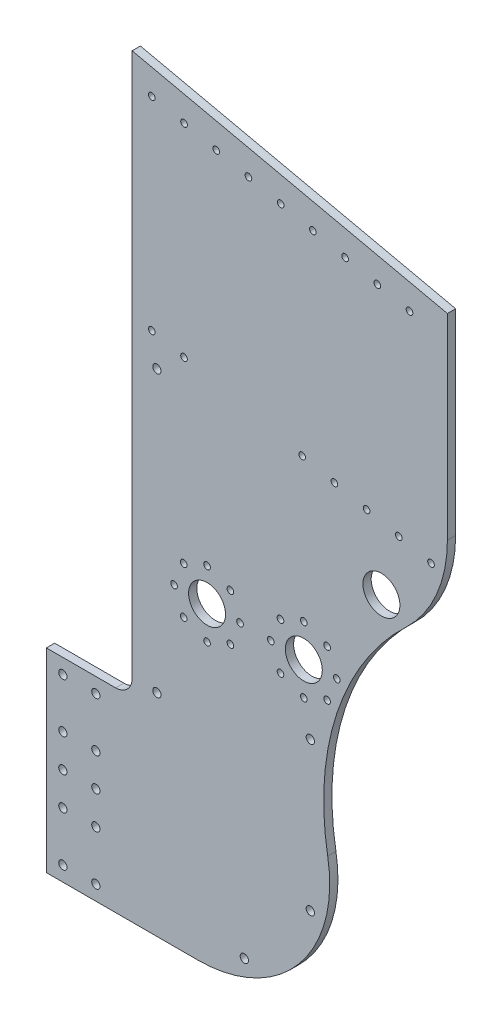
SolidWorks part; units mm, degrees
ref_plane "Front Plane" through (0, 0, 0) normal (0, 0, 1) x (1, 0, 0)
ref_plane "Top Plane" through (0, 0, 0) normal (0, 1, 0) x (1, 0, 0)
ref_plane "Right Plane" through (0, 0, 0) normal (1, 0, 0) x (0, 0, -1)
sketch "Sketch1" plane through (0, 0, 0) normal (0, 0, 1) x (1, 0, 0)
  line L1 (0, 0) -> (308.737, 0)
  line L2 (0, 0) -> (0, 580.9742)
  line L3 (0, 580.9742) -> (308.737, 580.9742)
  line L4 (308.737, 0) -> (308.737, 580.9742)
  dimension "D1" = 580.9742
  dimension "D2" = 308.737
extrude "Boss-Extrude1 (Stock)" add sketch "Sketch1" along normal blind 6.35
sketch "Sketch2" plane through (0, 0, 6.35) normal (0, 0, 1) x (1, 0, 0)
  line L0 (12.7, 11.43) -> (12.7, 49.53) construction
  line L1 (12.7, 49.53) -> (12.7, 74.93) construction
  line L2 (12.7, 74.93) -> (12.7, 100.33) construction
  line L4 (12.7, 100.33) -> (12.7, 138.43) construction
  line L5 (0, 0) -> (308.737, 0) construction
  line L6 (0, 580.9742) -> (0, 0) construction
  line L7 (25.4, 74.93) -> (25.4, 100.33) construction
  line L8 (12.7, 100.33) -> (25.4, 100.33) construction
  circle A0 centre (12.7, 11.43) radius 3.175
  circle A1 centre (12.7, 49.53) radius 3.175
  circle A2 centre (12.7, 74.93) radius 3.175
  circle A4 centre (12.7, 100.33) radius 3.175
  circle A5 centre (12.7, 138.43) radius 3.175
  circle A6 centre (38.1, 11.43) radius 3.175
  circle A7 centre (38.1, 49.53) radius 3.175
  circle A8 centre (38.1, 74.93) radius 3.175
  circle A9 centre (38.1, 100.33) radius 3.175
  circle A10 centre (38.1, 138.43) radius 3.175
  dimension "D6" = 6.35
  dimension "D1" = 11.43
  dimension "D2" = 12.7
  dimension "D3" = 38.1
  dimension "D4" = 25.4
  dimension "D5" = 12.7
extrude "Cut-Extrude1 (Mounting)" cut sketch "Sketch2" against normal through all both and the other way through all
sketch "Sketch3" plane through (0, 0, 6.35) normal (0, 0, 1) x (1, 0, 0)
  line L1 (0, 580.9742) -> (66.04, 580.9742)
  line L2 (0, 580.9742) -> (0, 149.86)
  line L3 (0, 149.86) -> (66.04, 149.86)
  line L4 (66.04, 580.9742) -> (66.04, 149.86)
  circle A0 centre (38.1, 138.43) radius 3.175 construction
  dimension "D1" = 11.43
  dimension "D2" = 66.04
extrude "Cut-Extrude2 (Elevator Clearance)" cut sketch "Sketch3" against normal through all both and the other way through all
sketch "Sketch4" plane through (0, 0, 6.35) normal (0, 0, 1) x (1, 0, 0)
  line L0 (66.04, 580.9742) -> (308.737, 527.1696)
  line L1 (308.737, 0) -> (308.737, 580.9742) construction
  line L2 (308.737, 527.1696) -> (308.737, 580.9742)
  line L3 (308.737, 580.9742) -> (66.04, 580.9742) construction
  line L4 (308.737, 580.9742) -> (66.04, 580.9742)
  dimension "D1" = 12.5
extrude "Cut-Extrude3 (Scorer Angle Material Removal)" cut sketch "Sketch4" against normal through all both and the other way through all
sketch "Sketch5" plane through (0, 0, 6.35) normal (0, 0, 1) x (1, 0, 0)
  line L0 (123.7136, 241.0793) -> (198.1975, 241.0793) construction
  circle A0 centre (198.1975, 241.0793) radius 14.224
  circle A1 centre (257.937, 314.325) radius 14.224
  circle A2 centre (12.7, 11.43) radius 3.175 construction
  circle A3 centre (123.7136, 241.0793) radius 14.224
  dimension "D1" = 28.448
  dimension "D3" = 302.895
  dimension "D4" = 59.7395
  dimension "D5" = 73.2457
  dimension "D2" = 245.237
  dimension "D6" = 152.908
extrude "Cut-Extrude4 (Algae Bearing Holes)" cut sketch "Sketch5" against normal through all both and the other way through all
sketch "Sketch6" plane through (0, 0, 6.35) normal (0, 0, 1) x (1, 0, 0)
  line L1 (180.237, 223.1188) -> (216.158, 223.1188) construction
  line L2 (180.237, 223.1188) -> (180.237, 259.0398) construction
  line L3 (180.237, 259.0398) -> (216.158, 259.0398) construction
  line L4 (216.158, 223.1188) -> (216.158, 259.0398) construction
  line L5 (180.237, 223.1188) -> (216.158, 259.0398) construction
  line L6 (180.237, 259.0398) -> (216.158, 223.1188) construction
  line L7 (105.7531, 223.1188) -> (141.6741, 223.1188) construction
  line L8 (105.7531, 223.1188) -> (105.7531, 259.0398) construction
  line L9 (105.7531, 259.0398) -> (141.6741, 259.0398) construction
  line L10 (141.6741, 223.1188) -> (141.6741, 259.0398) construction
  line L11 (105.7531, 223.1188) -> (141.6741, 259.0398) construction
  line L12 (105.7531, 259.0398) -> (141.6741, 223.1188) construction
  circle A0 centre (216.158, 259.0398) radius 2.5527
  circle A1 centre (180.237, 259.0398) radius 2.5527
  circle A2 centre (180.237, 223.1188) radius 2.5527
  circle A3 centre (216.158, 223.1188) radius 2.5527
  circle A4 centre (141.6741, 259.0398) radius 2.5527
  circle A5 centre (141.6741, 223.1188) radius 2.5527
  circle A6 centre (105.7531, 223.1188) radius 2.5527
  circle A7 centre (105.7531, 259.0398) radius 2.5527
  point P0 (198.1975, 241.0793)
  point P10 (123.7136, 241.0793)
  dimension "D2" = 5.1054
  dimension "D1" = 50.8
extrude "Cut-Extrude5 (Motor Mounting Holes)" cut sketch "Sketch6" against normal through all both and the other way through all
sketch "Sketch7" plane through (0, 0, 6.35) normal (0, 0, 1) x (1, 0, 0)
  circle A0 centre (416.687, 154.686) radius 203.2
  circle A1 centre (257.937, 314.325) radius 14.224 construction
  dimension "D2" = 158.75
  dimension "D3" = 406.4
  dimension "D1" = 159.639
extrude "Cut-Extrude6 (Algae Fitment)" cut sketch "Sketch7" against normal through all both and the other way through all
sketch "Sketch8" plane through (0, 0, 6.35) normal (0, 0, 1) x (1, 0, 0)
  line L0 (81.1877, 558.1035) -> (105.9857, 552.6059) construction
  line L1 (308.737, 527.1696) -> (66.04, 580.9742) construction
  line L2 (81.1877, 558.1035) -> (66.04, 561.4617) construction
  line L3 (66.04, 580.9742) -> (66.04, 149.86) construction
  line L6 (81.1877, 402.0033) -> (105.9857, 396.5057) construction
  line L7 (105.9857, 396.5057) -> (196.9376, 376.3422) construction
  line L8 (221.7355, 370.8446) -> (196.9376, 376.3422) construction
  circle A0 centre (81.1877, 558.1035) radius 2.5527
  circle A9 centre (105.9857, 396.5057) radius 2.5527
  circle A10 centre (81.1877, 402.0033) radius 2.5527
  circle A13 centre (196.9376, 376.3422) radius 2.5527
  circle A14 centre (221.7355, 370.8446) radius 2.5527
  circle A15 centre (246.5334, 365.347) radius 2.5527
  circle A16 centre (271.3313, 359.8495) radius 2.5527
  circle A17 centre (296.1293, 354.3519) radius 2.5527
  circle A18 centre (105.9857, 552.6059) radius 2.5527
  circle A19 centre (130.7836, 547.1084) radius 2.5527
  circle A20 centre (155.5815, 541.6108) radius 2.5527
  circle A21 centre (180.3794, 536.1132) radius 2.5527
  circle A22 centre (205.1773, 530.6157) radius 2.5527
  circle A23 centre (229.9753, 525.1181) radius 2.5527
  circle A24 centre (254.7732, 519.6205) radius 2.5527
  circle A25 centre (279.5711, 514.123) radius 2.5527
  dimension "D1" = 5.1054
  dimension "D6" = 156.1002
  dimension "D11" = 5.1054
  dimension "D2" = 19.05
  dimension "D4" = 25.4
  dimension "D5" = 25.4
  dimension "D7" = 93.1602
  dimension "D9" = 15.1477
  dimension "D10" = 25.4
  dimension "D12" = 15.1477
  dimension "D8" = 5
extrude "Cut-Extrude7 (Top/Bottom Mounting)" cut sketch "Sketch8" against normal through all both and the other way through all
fillet "Fillet1" radius 101.6 1 edges at (308.737, 326.8401, 3.175)
fillet "Fillet2" radius 101.6 1 edges at (284.9202, 0, 3.175)
fillet "Fillet3" radius 12.7 1 edges at (66.04, 149.86, 3.175)
sketch "Sketch9" plane through (0, 0, 6.35) normal (0, 0, 1) x (1, 0, 0)
  line L0 (85.09, 378.46) -> (85.09, 162.56) construction
  line L2 (85.09, 162.56) -> (66.04, 162.56) construction
  line L3 (0, 149.86) -> (0, 0) construction
  line L4 (0, 0) -> (116.5455, 0) construction
  circle A0 centre (85.09, 162.56) radius 3.175
  circle A1 centre (152.4, 19.05) radius 3.175
  circle A2 centre (203.2, 76.2) radius 3.175
  circle A3 centre (85.09, 378.46) radius 3.175
  circle A4 centre (203.2, 190.5) radius 3.175
  dimension "D1" = 6.35
  dimension "D8" = 203.2
  dimension "D2" = 19.05
  dimension "D3" = 215.9
  dimension "D4" = 152.4
  dimension "D5" = 76.2
  dimension "D6" = 203.2
  dimension "D7" = 19.05
  dimension "D9" = 114.3
extrude "Cut-Extrude1" cut sketch "Sketch9" against normal through all both and the other way through all
sketch "Sketch11" plane through (0, 0, 6.35) normal (0, 0, 1) x (1, 0, 0)
  circle A0 centre (198.1974, 266.4793) radius 2.5527
  circle A1 centre (223.5975, 241.0793) radius 2.5527
  circle A2 centre (172.7975, 241.0793) radius 2.5527
  circle A3 centre (198.1974, 215.6793) radius 2.5527
  circle A4 centre (198.1975, 241.0793) radius 14.224 construction
  point P10 (172.7975, 241.0793)
  point P13 (223.5975, 241.0793)
  dimension "D1" = 25.4
  dimension "D2" = 25.4
  dimension "D3" = 25.4
  dimension "D4" = 25.4
  dimension "D5" = 5.1054
  dimension "D6" = 5.1054
  dimension "D7" = 5.1054
  dimension "D8" = 5.1054
extrude "Cut-Extrude2" cut sketch "Sketch11" against normal through all both and the other way through all
sketch "Sketch12" plane through (0, 0, 6.35) normal (0, 0, 1) x (1, 0, 0)
  circle A0 centre (123.7136, 266.4793) radius 2.5527
  circle A1 centre (123.7136, 241.0793) radius 14.224 construction
  circle A2 centre (149.1136, 241.0793) radius 2.5527
  circle A3 centre (123.7136, 215.6793) radius 2.5527
  circle A4 centre (98.3136, 241.0792) radius 2.5527
  point P13 (123.7136, 241.0793)
  dimension "D1" = 5.1054
  dimension "D2" = 25.4
  dimension "D3" = 4
extrude "Cut-Extrude3" cut sketch "Sketch12" against normal through all both and the other way through all
